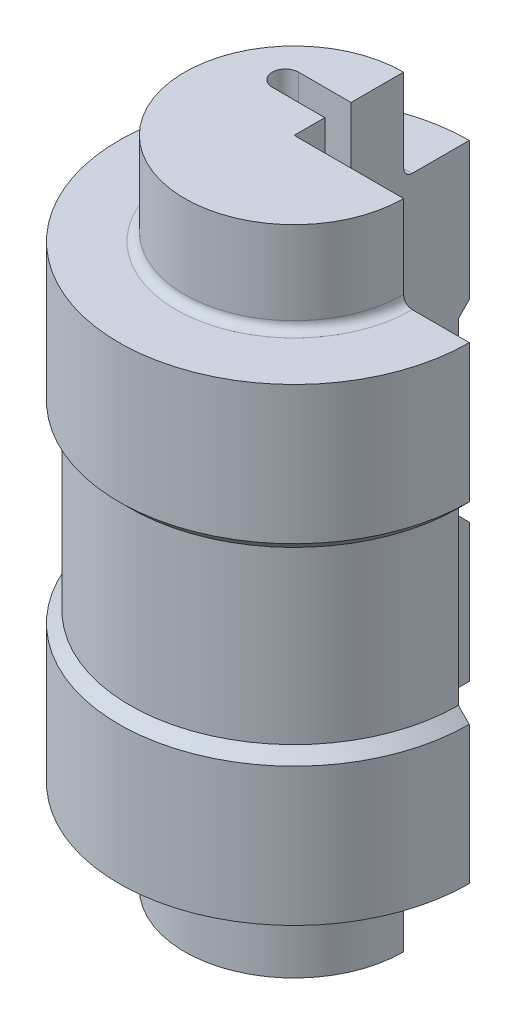
SolidWorks part; units mm, degrees
material "AISI 1020"
ref_plane "Front Plane" through (0, 0, 0) normal (0, 0, 1) x (1, 0, 0)
ref_plane "Top Plane" through (0, 0, 0) normal (0, 1, 0) x (1, 0, 0)
ref_plane "Right Plane" through (0, 0, 0) normal (1, 0, 0) x (0, 0, -1)
sketch "Sketch1" plane through (0, 0, 0) normal (0, 1, 0) x (1, 0, 0)
  circle A0 centre (0, 0) radius 40
  dimension "D1" = 80
extrude "Boss-Extrude1" add sketch "Sketch1" along normal mid plane 149
sketch "Sketch3" plane through (0, 74.5, 0) normal (0, 1, 0) x (1, 0, 0)
  circle A0 centre (0, 0) radius 25
  circle A1 centre (0, 0) radius 40 construction
  circle A2 centre (0, 0) radius 40
  dimension "D1" = 50
extrude "Cut-Extrude1" cut sketch "Sketch3" against normal blind 21 contours A2 | A0
mirror "Mirror1" about plane through (0, 0, 0) normal (0, 1, 0) of "Cut-Extrude1"
sketch "Sketch2" plane through (0, 0, 0) normal (0, 1, 0) x (1, 0, 0)
  circle A0 centre (0, 0) radius 37.5
  circle A1 centre (0, 0) radius 40 construction
  circle A2 centre (0, 0) radius 40
  dimension "D1" = 75
extrude "Cut-Extrude2" cut sketch "Sketch2" along normal offset from surface 31.5 and the other way offset from surface (22 mm away) 31.5 up to face at (0, 53.5, 25) other way up to face at (0, -53.5, 40)
sketch "Sketch5" plane through (0, 74.5, 0) normal (0, 1, 0) x (1, 0, 0)
  line L0 (0, -53.6027) -> (0, 7) construction
  line L1 (-43.3294, 0) -> (45.1465, 0) construction
  line L2 (-12, 10) -> (12, 10) construction
  line L3 (-12, 13) -> (12, 13)
  line L4 (-12, 7) -> (12, 7)
  line L6 (0, 13) -> (0, 49.2698) construction
  arc A0 (-12, 13) -> (-12, 7) centre (-12, 10) ccw
  arc A1 (12, 7) -> (12, 13) centre (12, 10) ccw
  point P7 (0, 10)
  dimension "D1" = 3
  dimension "D2" = 12
  dimension "D3" = 7
extrude "Cut-Extrude4" cut sketch "Sketch5" against normal through all
fillet "Fillet1" radius 2 2 edges at (0, -53.5, 25) (0, 53.5, 25)
chamfer "Chamfer1" [suppressed] distance 2.5 angle 45
sketch "Sketch7" plane through (0, 0, 0) normal (1, 0, 0) x (0, 0, -1)
  line L0 (40, 22) -> (37.5, 19.5)
  line L1 (37.5, -22) -> (37.5, 22) construction
  line L2 (40, 22) -> (40, 53.5) construction
  line L3 (40, 22) -> (37.5, 22)
  line L4 (37.5, 22) -> (37.5, 19.5)
  line L5 (0, 103.8814) -> (0, -88.9255) construction
  dimension "D1" = 45
  dimension "D2" = 2.5
revolve "Revolve2" add sketch "Sketch7" angle 360 about L5
mirror "Mirror2" about plane through (0, 0, 0) normal (0, 1, 0) of "Revolve2"
sketch "Sketch4" plane through (0, 74.5, 0) normal (0, 1, 0) x (1, 0, 0)
  line L0 (0, 0) -> (0, 40)
  line L1 (0, 0) -> (40, 0)
  circle A0 centre (0, 0) radius 40 construction
  arc A1 (40, 0) -> (0, 40) centre (0, 0) ccw
extrude "Cut-Extrude5" cut sketch "Sketch4" against normal through all
equation "\"A\"= 149"
equation "\"B\"= 21"
equation "\"C\" = 31.5"
equation "\"D1@Boss-Extrude1\"=\"A\""
equation "\"D1@Cut-Extrude1\"=\"B\""
equation "\"D1@Cut-Extrude2\"=\"C\""
equation "\"D2@Cut-Extrude2\"=\"C\""
